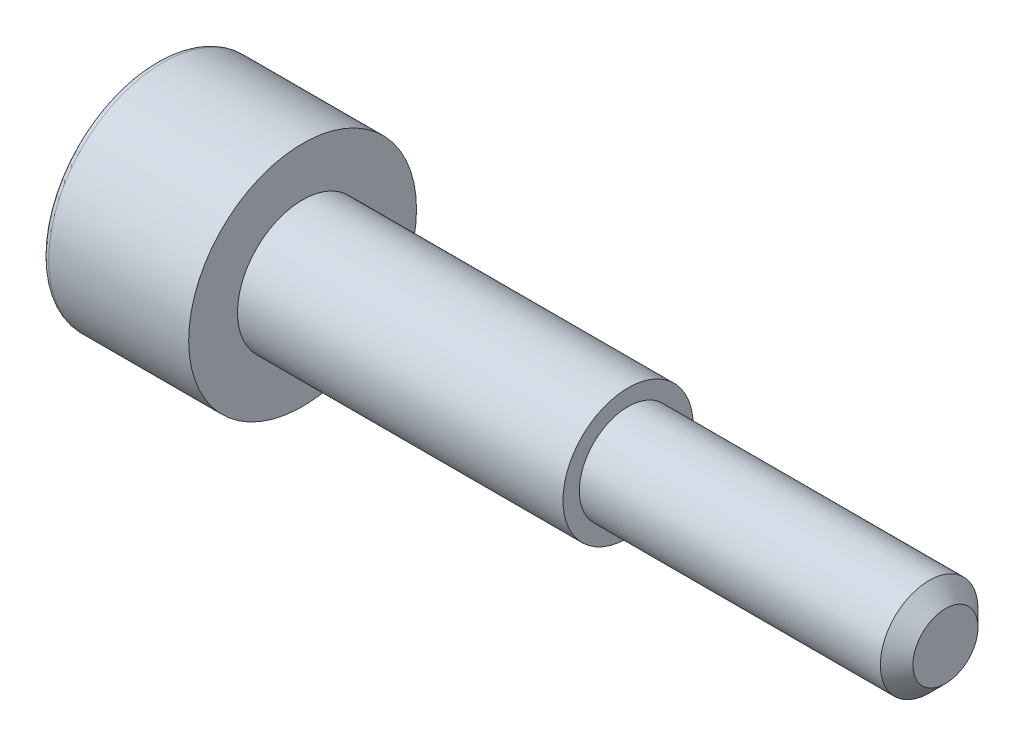
SolidWorks part; units mm, degrees
ref_plane "Front" through (0, 0, 0) normal (0, 0, 1) x (1, 0, 0)
ref_plane "Top" through (0, 0, 0) normal (0, 1, 0) x (1, 0, 0)
ref_plane "Right" through (0, 0, 0) normal (1, 0, 0) x (0, 0, -1)
sketch "Sketch1" plane through (0, 0, 0) normal (1, 0, 0) x (0, 0, -1)
  circle A0 centre (0, 0) radius 3.5
  dimension "dk" = 7
extrude "BaseHead" add sketch "Sketch1" along normal blind 4.5
sketch "Sketch2" plane through (4.5, 0, 0) normal (1, 0, 0) x (0, 0, -1)
  circle A0 centre (0, 0) radius 2
  dimension "ds" = 4
extrude "BaseBody" add sketch "Sketch2" along normal blind 10
sketch "Sketch3" plane through (14.5, 0, 0) normal (1, 0, 0) x (0, 0, -1)
  circle A0 centre (0, 0) radius 1.5
  dimension "d" = 3
extrude "BaseEnd" add sketch "Sketch3" along normal blind 9.75
cosmetic thread "ThreadCosmetic1" parameters "THD_MINOR"=4.134
sketch "Sketch5" plane through (0, 0, 0) normal (1, 0, 0) x (0, 0, -1)
  line L1 (1.7321, 0) -> (0.866, 1.5)
  line L2 (0.866, 1.5) -> (-0.866, 1.5)
  line L3 (-0.866, 1.5) -> (-1.7321, 0)
  line L4 (-1.7321, 0) -> (-0.866, -1.5)
  line L5 (-0.866, -1.5) -> (0.866, -1.5)
  line L6 (0.866, -1.5) -> (1.7321, 0)
  circle A0 centre (0, 0) radius 1.5 construction
  dimension "s" = 3
extrude "Socket" cut sketch "Sketch5" along normal blind 2.4
sketch "Sketch6" plane through (2.4, 0, 0) normal (-1, 0, 0) x (0, 0, 1)
  line L0 (1.7321, 0) -> (0.866, -1.5) construction
  line L1 (0.866, -1.5) -> (-0.866, -1.5) construction
  line L2 (-0.866, -1.5) -> (-1.7321, 0) construction
  line L3 (0.866, 1.5) -> (1.7321, 0) construction
  line L4 (-1.7321, 0) -> (-0.866, 1.5) construction
  line L5 (-0.866, 1.5) -> (0.866, 1.5) construction
  line L6 (1.7321, 0) -> (0.866, -1.5)
  line L7 (0.866, -1.5) -> (-0.866, -1.5)
  line L8 (-0.866, -1.5) -> (-1.7321, 0)
  line L9 (0.866, 1.5) -> (1.7321, 0)
  line L10 (-1.7321, 0) -> (-0.866, 1.5)
  line L11 (-0.866, 1.5) -> (0.866, 1.5)
extrude "Cut-Extrude2" cut sketch "Sketch6" against normal blind 10 draft 60
chamfer "Chamfer1" distance 0.5 angle 45 1 edges at (24.25, 0, -1.5)
fillet "HeadFillet" radius 0.2 1 edges at (0, 0, -3.5)
sketch "Sketch8" plane through (0, 0, 0) normal (0, 0, 1) x (1, 0, 0)
  line L0 (23.75, 1.009) -> (24.0335, 1.5)
  line L1 (24.0335, 1.5) -> (24.0335, 2.067)
  line L2 (24.0335, 2.067) -> (23.4665, 2.067)
  line L3 (23.4665, 2.067) -> (23.4665, 1.5)
  line L4 (23.4665, 1.5) -> (23.75, 1.009)
  line L5 (23.75, -1.5) -> (23.75, 1.5) construction
  line L6 (0, 0) -> (37.4968, 0) construction
  dimension "D1" = 3
  dimension "D2" = 0.567
revolve "Cut-Revolve10" [suppressed] cut sketch "Sketch8" angle 360 about L6
pattern_linear "LPattern10" [suppressed] count 15 spacing 0.5196 along (1, 0, 0)
equation "\"D1@Sketch8\" = \"d@Sketch3\""
equation "\"D2@Sketch8\" =  ( \"d@Sketch3\" - \"THD_MINOR@ThreadCosmetic1\" )  / 2"
equation "\"D3@LPattern10\" = \"D2@Sketch8\" * 1.2"
